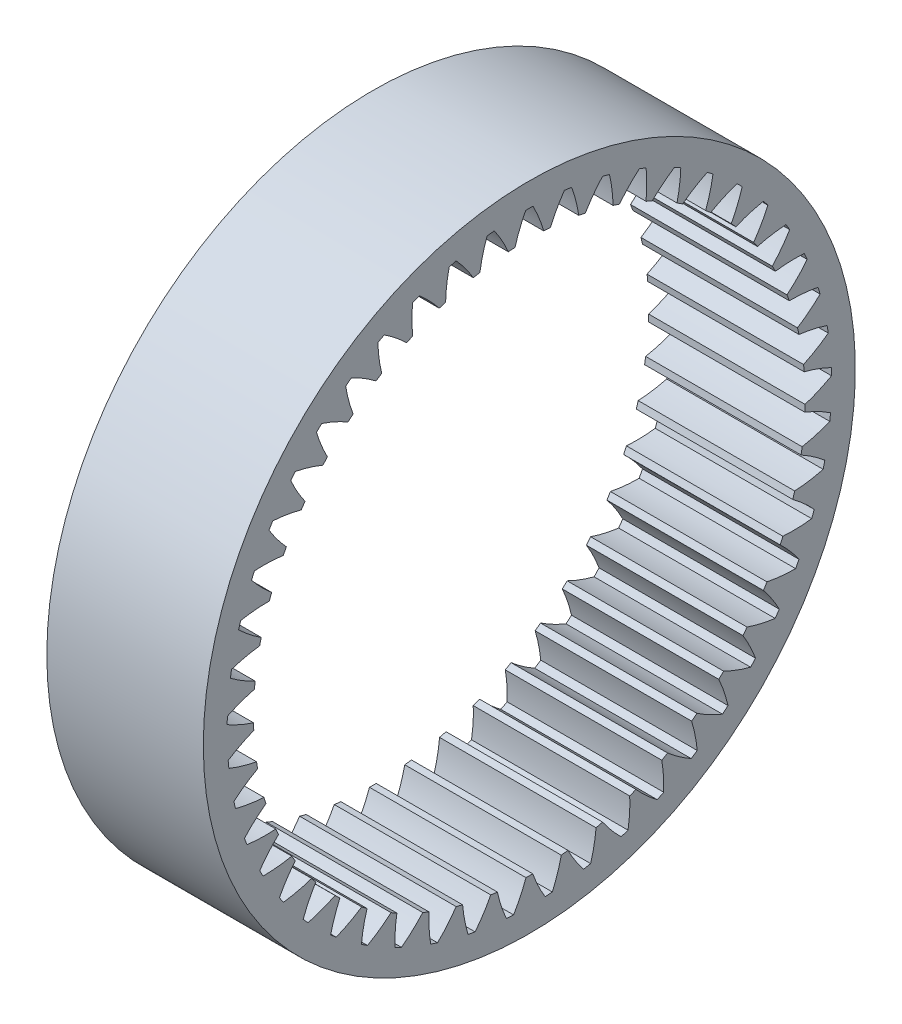
SolidWorks part; units mm, degrees
ref_plane "Plane1" through (0, 0, 0) normal (0, 0, 1) x (1, 0, 0)
ref_plane "Plane2" through (0, 0, 0) normal (0, 1, 0) x (1, 0, 0)
ref_plane "Plane3" through (0, 0, 0) normal (1, 0, 0) x (0, 0, -1)
other "Configuration Table"
sketch "HoldingSke" plane through (0, 0, 0) normal (0, 1, 0) x (1, 0, 0)
  line L0 (0, 0) -> (0.729, -0.8386)
  line L1 (-15, 0) -> (100, 0) construction
  line L2 (0, 0) -> (-2.1039, 2.3779)
  line L3 (0, 0) -> (-11.863, 4.5341)
  line L4 (0, 0) -> (5.6657, 6.5177)
  line L5 (0, 0) -> (-23.7986, -8.8762)
  line L6 (0, 0) -> (-10.5278, -7.1032)
  line L7 (-2.1039, 2.3779) -> (3.3635, 27.1825)
  line L8 (-76.2, 3.2779) -> (-54.61, 3.2779)
  line L9 (-71.009, 38.7566) -> (-53.1078, 45.2721)
  line L10 (-76.2, 71.12) -> (104.1128, 71.12)
  line L11 (0, 0) -> (-12, 0)
  line L12 (-76.2, 101.6) -> (-76.166, 101.6)
  line L13 (24.9733, 27.94) -> (52.9518, 28.4284)
  line L14 (24.9733, 27.94) -> (24.9743, 27.94)
  line L15 (24.9733, 27.94) -> (100.4006, 29.5858)
  circle A0 centre (0, 0) radius 25
  circle A1 centre (0, 0) radius 12.7
  circle A2 centre (0, 0) radius 12.7
  dimension "MHD" = 25.4
  dimension "Hub_dia" = 25.4
  dimension "Diameter" = 50
  dimension "Num_teeth" = 49
  dimension "Pitch" = 1.1111
  dimension "Overall_len" = 25.4
  dimension "Show_teeth" = 49
  dimension "Thickness" = 12.7
  dimension "OAL" = 25.4001
  dimension "T_dim" = 21.59
  dimension "Ap" = 20
  dimension "H" = 19.05
  dimension "Pitch_radius" = 180.3128
  dimension "Width" = 12
  dimension "Backlash" = 0.034
  dimension "Addendum_fac" = 1
  dimension "Dedendum_fac" = 1.25
  dimension "Clearance_fac" = 0.25
  dimension "Dedendum_add" = 0.001
  dimension "Module" = 0.9
sketch "BasProSke" plane through (0, 0, 0) normal (0, 1, 0) x (1, 0, 0)
  line L0 (-10, 0) -> (60, 0) construction
  line L1 (0, 21.15) -> (0, 25)
  line L2 (0, 21.15) -> (12, 21.15)
  line L3 (12, 21.15) -> (12, 25)
  line L4 (12, 25) -> (0, 25)
  dimension "Diameter" = 50
  dimension "Thickness" = 12
  dimension "Inside_diameter" = 42.3
revolve "Base-Revolve" add sketch "BasProSke" angle 360 about L0
sketch "TooCutSke" plane through (0, 0, 0) normal (1, 0, 0) x (0, 0, -1)
  line L3 (0.7917, 22.0358) -> (0.7917, 53.6633) construction
  line L4 (0, 0) -> (0, 59.563) construction
  line L5 (0, 0) -> (-4.3778, 68.1871) construction
  line L6 (-9.4979, 18.0768) -> (36.5703, 21.0345) construction
  circle A0 centre (0, 0) radius 22.05 construction
  circle A1 centre (0, 0) radius 23.176 construction
  circle A2 centre (0, 0) radius 18.6482 construction
  circle A3 centre (0, 0) radius 21.1246 construction
  arc A4 (1.1057, 21.0956) -> (0.2779, 23.1743) centre (-9.4979, 18.0768) ccw
  arc A5 (1.1057, 21.0956) -> (-1.1057, 21.0956) centre (0, 0) ccw
  arc A6 (0.2779, 23.1743) -> (-0.2779, 23.1743) centre (0, 0) ccw
  arc A7 (-0.2779, 23.1743) -> (-1.1057, 21.0956) centre (9.4979, 18.0768) ccw
  dimension "Pitch_dia" = 44.1
  dimension "Base_dia" = 37.2964
  dimension "Root_dia" = 46.352
  dimension "Overcut_dia" = 42.2492
  dimension "Flank_rad" = 11.025
  dimension "Half_ang" = 3.673
  dimension "Half_CT" = 0.7917
extrude "ToothCut" cut sketch "TooCutSke" along normal through all
fillet "Breaks" [suppressed] radius 0.09
fillet "RootFillets" [suppressed] radius 0.226
pattern_circular "TeethCuts" count 49 every 7.347 about axis through (-10, 0, 0) along (1, 0, 0) of "RootFillets", "Breaks", "ToothCut"
sketch "Sketch1" plane through (12, 0, 0) normal (1, 0, 0) x (0, 0, -1)
  circle A0 centre (0, 0) radius 22.25
  dimension "D1" = 44.5
equation "' \"Module@HoldingSke\" = 6.35"
equation "' \"Num_teeth@HoldingSke\" = 24"
equation "' \"Ap@HoldingSke\" =  14.5"
equation "' \"Ap@HoldingSke\" = 14.5"
equation "' \"Width@HoldingSke\" = 12"
equation "' \"Diameter@HoldingSke\" = 8 * 25.4"
equation "' \"Show_teeth@HoldingSke\" = 100"
equation "' \"Backlash@HoldingSke\" = 0.009 * 25.4"
equation "' \"Addendum_fac@HoldingSke\" = 1.0"
equation "' \"Dedendum_fac@HoldingSke\" = 1.25"
equation "' \"Dedendum_add@HoldingSke\" = 0.00005 * 25.4"
equation "' \"Clearance_fac@HoldingSke\" = 0.25"
equation "\"Pitch@HoldingSke\" = 1 / \"Module@HoldingSke\" "
equation "\"Overcut_dia@TooCutSke\" = (\"Num_teeth@HoldingSke\" - 2 * \"Addendum_fac@HoldingSke\") / \"Pitch@HoldingSke\" - 0.002 * 25.4"
equation "\"Pitch_dia@TooCutSke\" = \"Num_teeth@HoldingSke\" / \"Pitch@HoldingSke\""
equation "\"Base_dia@TooCutSke\" = \"Num_teeth@HoldingSke\" / \"Pitch@HoldingSke\" * cos((\"Ap@HoldingSke\"  * 3.14159265 / 180)) * 0.90"
equation "\"Root_dia@TooCutSke\" = \"Num_teeth@HoldingSke\"  / \"Pitch@HoldingSke\" + 2 *  \"Dedendum_fac@HoldingSke\"/ \"Pitch@HoldingSke\" + \"Dedendum_add@HoldingSke\" * 2"
equation "\"Half_ang@TooCutSke\" = 180 / \"Num_teeth@HoldingSke\""
equation "\"Half_CT@TooCutSke\" = \"Num_teeth@HoldingSke\" / \"Pitch@HoldingSke\" * sin((3.14159265 / 2 / \"Num_teeth@HoldingSke\")) / 2 + 10 * \"Backlash@HoldingSke\" / 4"
equation "\"Flank_rad@TooCutSke\" = \"Num_teeth@HoldingSke\" / \"Pitch@HoldingSke\" / 4"
equation "\"Radius@RootFillets\"= \"Clearance_fac@HoldingSke\" / \"Pitch@HoldingSke\" + \"Dedendum_add@HoldingSke\""
equation "\"Break_rad@Breaks\" = 0.02 / \"Pitch@HoldingSke\" * 5"
equation "\"Num_teeth@TeethCuts\" = int( \"Show_teeth@HoldingSke\" ) + 1"
equation "\"Num_teeth@TeethCuts\" = ((sgn( \"Num_teeth@TeethCuts\" - \"Num_teeth@HoldingSke\" )-1)*( \"Num_teeth@TeethCuts\" - \"Num_teeth@HoldingSke\" ))/-2+ \"Num_teeth@HoldingSke\""
equation "\"Num_teeth@TeethCuts\" = ((sgn( \"Num_teeth@TeethCuts\" - 2.0)+1)*( \"Num_teeth@TeethCuts\" - 2.0))/2 +2.0"
equation "\"Angle@TeethCuts\" = 360.0 / \"Num_teeth@HoldingSke\""
equation "\"Diameter@BasProSke\" = \"Num_teeth@HoldingSke\"  / \"Pitch@HoldingSke\" + 2 *  \"Dedendum_fac@HoldingSke\"/ \"Pitch@HoldingSke\" + \"Dedendum_add@HoldingSke\" * 2 + 0.002 * 25.4"
equation "\"Diameter@BasProSke\" = ((sgn( \"Diameter@BasProSke\"  - \"Diameter@HoldingSke\" )+1)*( \"Diameter@BasProSke\"  - \"Diameter@HoldingSke\" ))/2 + \"Diameter@HoldingSke\""
equation "\"Inside_diameter@BasProSke\" =  (\"Num_teeth@HoldingSke\" - 2 * \"Addendum_fac@HoldingSke\") / \"Pitch@HoldingSke\" "
equation "\"Thickness@BasProSke\"  = \"Width@HoldingSke\""
